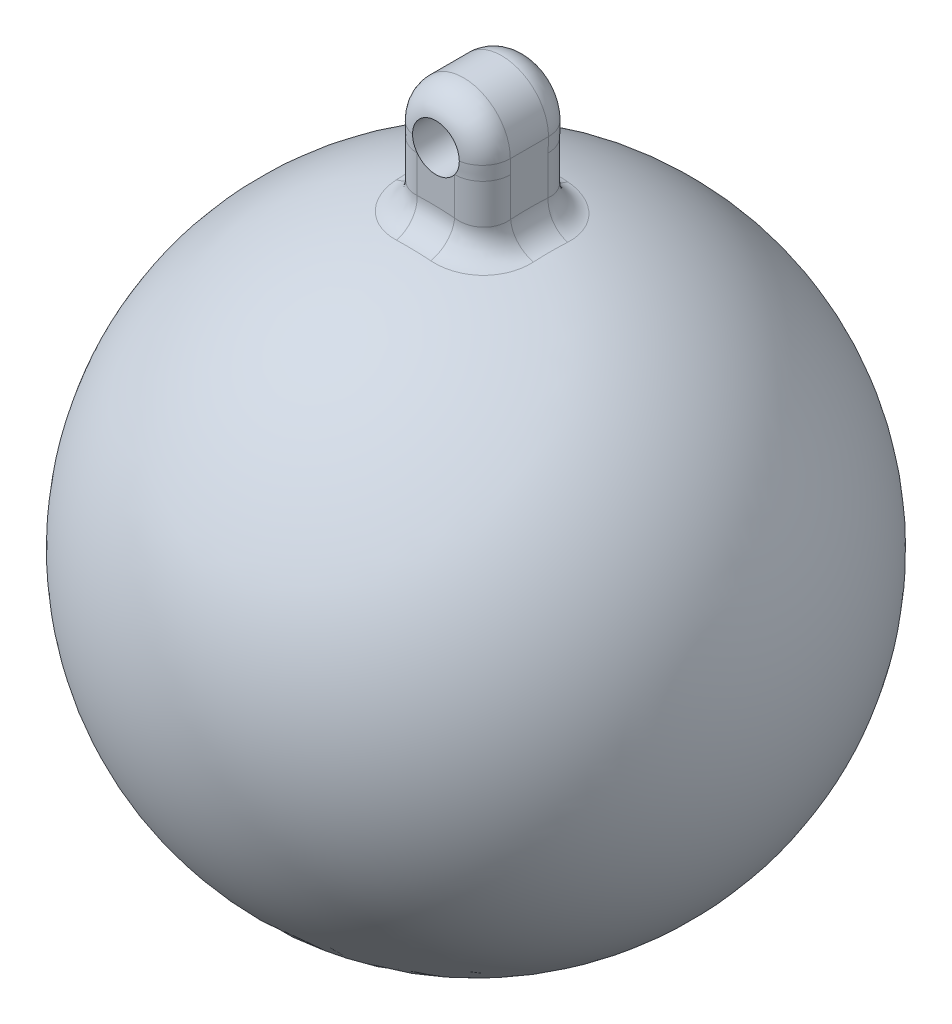
SolidWorks part; units mm, degrees
ref_plane "Front Plane" through (0, 0, 0) normal (0, 0, 1) x (1, 0, 0)
ref_plane "Top Plane" through (0, 0, 0) normal (0, 1, 0) x (1, 0, 0)
ref_plane "Right Plane" through (0, 0, 0) normal (1, 0, 0) x (0, 0, -1)
sketch "Sketch1" plane through (0, 0, 0) normal (0, 1, 0) x (1, 0, 0)
  line L0 (-32.5, 0) -> (32.5, 0)
  arc A0 (-32.5, 0) -> (32.5, 0) centre (0, 0) ccw
  dimension "D1" = 32.5
revolve "Revolve1" add sketch "Sketch1" angle 360 about L0
sketch "Sketch2" plane through (0, 0, 0) normal (0, 0, 1) x (1, 0, 0)
  line L2 (-4.2876, 40) -> (-4.2876, 25)
  line L3 (-4.2876, 25) -> (5.7124, 25)
  line L4 (5.7124, 40) -> (5.7124, 25)
  line L5 (-4.2876, 40) -> (5.7124, 25) construction
  line L6 (-4.2876, 25) -> (5.7124, 40) construction
  arc A0 (-4.2876, 40) -> (5.7124, 40) centre (0.7124, 40) cw
  circle A1 centre (0.7124, 40) radius 2.5
  point P0 (0.7124, 32.5)
  dimension "D3" = 5
  dimension "D1" = 25
  dimension "D2" = 10
  dimension "D4" = 15
extrude "Boss-Extrude1" add sketch "Sketch2" along normal mid plane 10 contours L2 L3 L4 A0
sketch "Sketch3" plane through (0, 0, 5) normal (0, 0, 1) x (1, 0, 0)
  circle A0 centre (0.7124, 40) radius 2.5
  dimension "D1" = 5
extrude "Cut-Extrude1" cut sketch "Sketch3" against normal blind 10
fillet "Fillet7" radius 3 8 edges at (-4.2876, 32.2159, 0) (5.7124, 31.994, 0) (-4.2876, 35.9128, -5) (5.7124, 35.8005, -5) (-4.2876, 35.9128, 5) (5.7124, 35.8005, 5) (0.7212, 32.105, -5) (0.7212, 32.105, 5)
